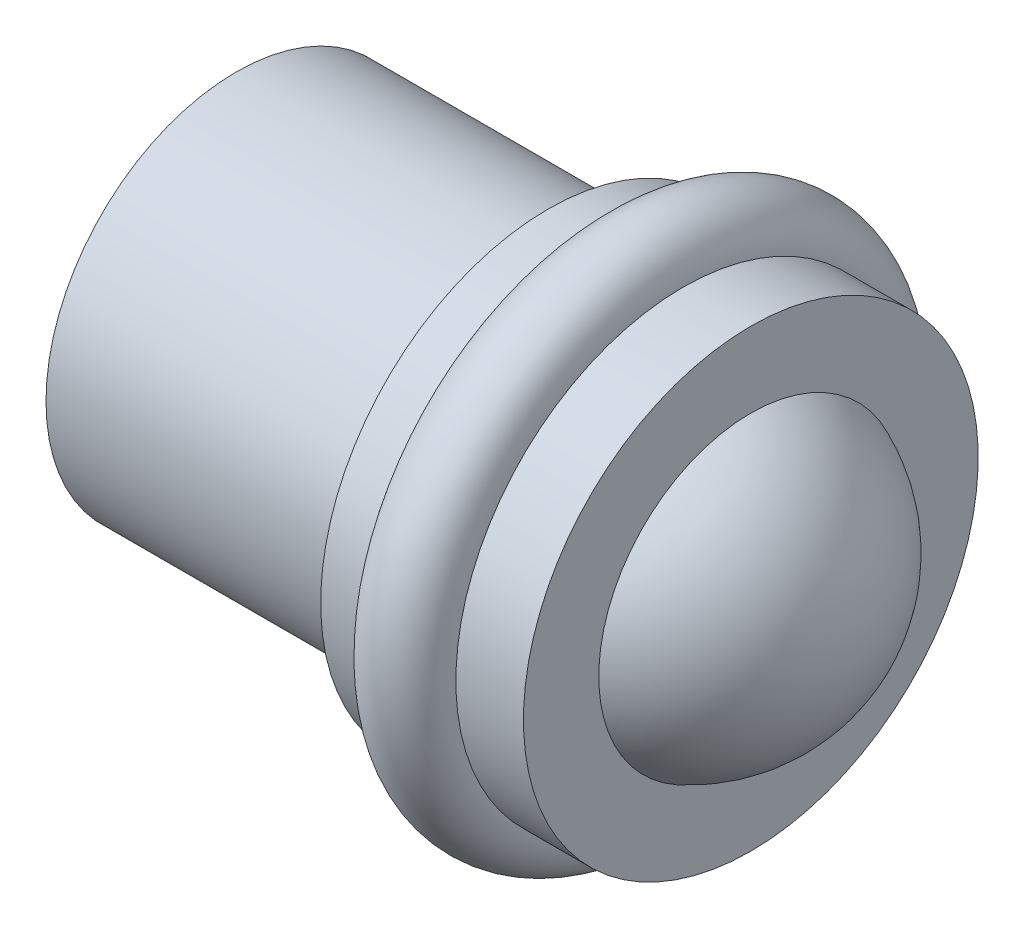
SolidWorks part; units mm, degrees
material "Plain Carbon Steel"
ref_plane "Front Plane" through (0, 0, 0) normal (0, 0, 1) x (1, 0, 0)
ref_plane "Top Plane" through (0, 0, 0) normal (0, 1, 0) x (1, 0, 0)
ref_plane "Right Plane" through (0, 0, 0) normal (1, 0, 0) x (0, 0, -1)
sketch "Sketch1" plane through (0, 0, 0) normal (0, 0, 1) x (1, 0, 0)
  line L0 (-8.1153, 0) -> (8.1153, 0) construction
  line L1 (-8.1153, 0) -> (-8.1153, 5.0038)
  line L2 (-8.1153, 5.0038) -> (0.0889, 5.0038)
  line L3 (0.0889, 5.0038) -> (0.0889, 5.9817)
  line L4 (0.0889, 5.9817) -> (1.4224, 5.9817)
  line L5 (3.6449, 5.9817) -> (5.4229, 5.9817)
  line L6 (5.4229, 5.9817) -> (5.4229, 4.0005)
  line L7 (-8.1153, 0) -> (8.1153, 0)
  arc A0 (1.4224, 5.9817) -> (3.6449, 5.9817) centre (2.5336, 5.9817) ccw
  arc A1 (5.4229, 4.0005) -> (8.1153, 0) centre (3.797, 0) cw
  dimension "H" = 2.6924
  dimension "D2" = 10.0076
  dimension "D1" = 8.001
  dimension "D" = 11.9634
  dimension "L3" = 5.334
  dimension "L2" = 1.3335
  dimension "L1" = 1.778
  dimension "A" = 8.2042
revolve "Revolve1" add sketch "Sketch1" angle 360 about L0
sketch "Sketch2" plane through (0, 0, 0) normal (0, 0, 1) x (1, 0, 0)
  circle A0 centre (2.5336, 5.9817) radius 1.1112
  arc A1 (1.4224, 5.9817) -> (3.6449, 5.9817) centre (2.5336, 5.9817) ccw construction
revolve "Revolve2" add sketch "Sketch2" angle 360 about L7
equation "\"L2@Sketch1\" = \"L3@Sketch1\"/4"
equation "\"L1@Sketch1\" = \"L3@Sketch1\"/3"
